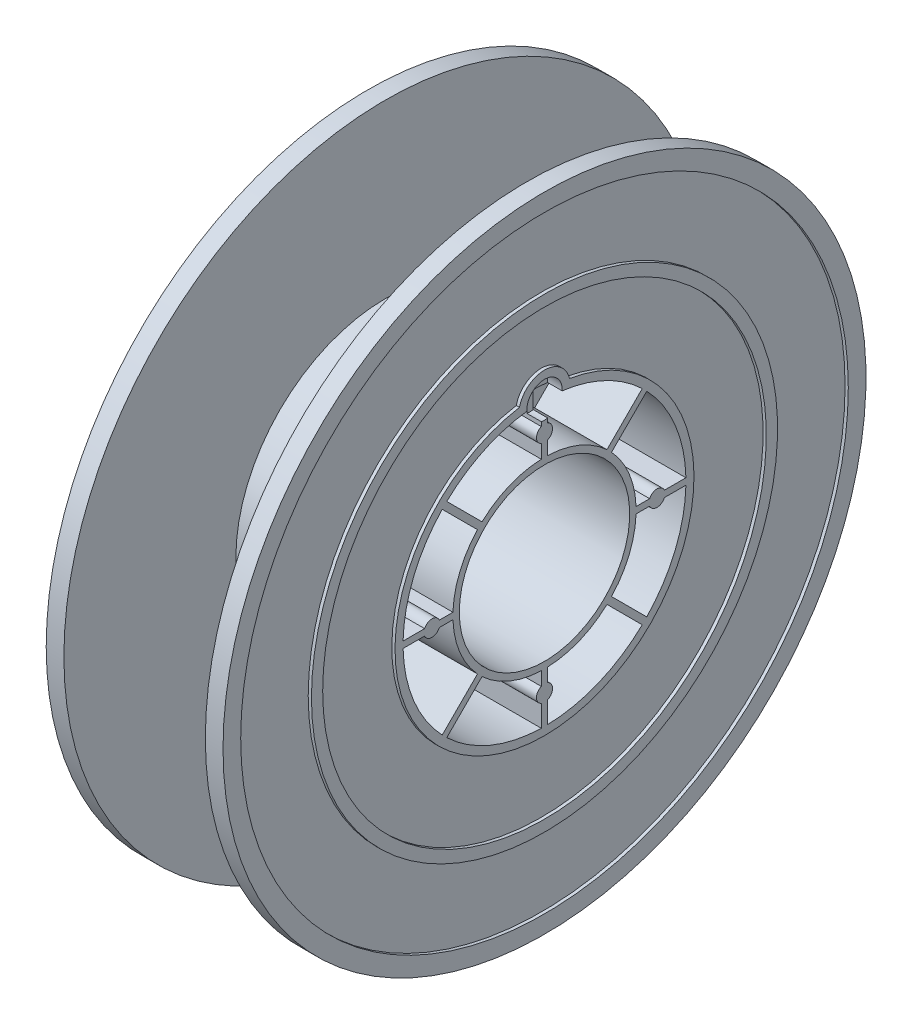
SolidWorks part; units mm, degrees
ref_plane "Front" through (0, 0, 0) normal (0, 0, 1) x (1, 0, 0)
ref_plane "Top" through (0, 0, 0) normal (0, 1, 0) x (1, 0, 0)
ref_plane "Right" through (0, 0, 0) normal (1, 0, 0) x (0, 0, -1)
sketch "Sketch1" plane through (0, 0, 0) normal (0, 0, 1) x (1, 0, 0)
  line L0 (0, 46.5) -> (0, 0) construction
  line L1 (0, 0) -> (80.9814, 0) construction
  line L2 (-27.5, 26.5) -> (27.5, 26.5)
  line L3 (27.5, 26.5) -> (27.5, 28.5)
  line L4 (27.5, 28.5) -> (-27.5, 28.5)
  line L5 (-22, 100) -> (-22, 46.5)
  line L6 (-27.5, 44) -> (27.5, 44)
  line L7 (27.5, 44) -> (27.5, 46.5)
  line L8 (27.5, 46.5) -> (26.5, 46.5)
  line L9 (26.5, 46.5) -> (26.5, 69)
  line L10 (26.5, 69) -> (27.5, 69)
  line L11 (27.5, 69) -> (27.5, 72.5)
  line L12 (27.5, 72.5) -> (26.5, 72.5)
  line L13 (26.5, 72.5) -> (26.5, 94.5)
  line L14 (27.5, 100) -> (27.5, 94.5)
  line L15 (27.5, 100) -> (22, 100)
  line L16 (22, 100) -> (22, 46.5)
  line L17 (22, 46.5) -> (-22, 46.5)
  line L18 (27.5, 94.5) -> (26.5, 94.5)
  line L19 (-27.5, 100) -> (-22, 100)
  line L20 (-27.5, 100) -> (-27.5, 94.5)
  line L21 (-27.5, 94.5) -> (-26.5, 94.5)
  line L22 (-26.5, 72.5) -> (-26.5, 94.5)
  line L23 (-27.5, 72.5) -> (-26.5, 72.5)
  line L24 (-27.5, 69) -> (-27.5, 72.5)
  line L25 (-26.5, 69) -> (-27.5, 69)
  line L26 (-26.5, 46.5) -> (-26.5, 69)
  line L27 (-27.5, 46.5) -> (-26.5, 46.5)
  line L28 (-27.5, 44) -> (-27.5, 46.5)
  line L29 (-27.5, 26.5) -> (-27.5, 28.5)
  dimension "D1" = 53
  dimension "D2" = 55
  dimension "D3" = 1
  dimension "D4" = 88
  dimension "D5" = 2.5
  dimension "D6" = 200
  dimension "D7" = 145
  dimension "D8" = 3.5
  dimension "D9" = 5.5
  dimension "D10" = 44
  dimension "D11" = 2
revolve "Revolve1" add sketch "Sketch1" angle 360 about L1
sketch "Sketch2" plane through (0, 0, 0) normal (1, 0, 0) x (0, 0, -1)
  circle A0 centre (0, 0) radius 46.5 construction
  circle A1 centre (0, 0) radius 46.5
  circle A2 centre (0, 0) radius 26.5 construction
  circle A3 centre (0, 0) radius 26.5
extrude "Boss-Extrude1" add sketch "Sketch2" along normal blind 2 from offset 3
sketch "Sketch3" plane through (-27.5, 0, 0) normal (-1, 0, 0) x (0, 0, 1)
  line L0 (0, 26.5) -> (0, 44)
  line L1 (0, -26.5) -> (0, -44)
  line L2 (26.5, 0) -> (44, 0)
  line L3 (-26.5, 0) -> (-44, 0)
  line L4 (-18.7383, 18.7383) -> (-31.1127, 31.1127)
  line L5 (18.7383, -18.7383) -> (31.1127, -31.1127)
  line L6 (18.7383, 18.7383) -> (31.1127, 31.1127)
  line L7 (-18.7383, -18.7383) -> (-31.1127, -31.1127)
  circle A0 centre (0, 0) radius 26.5 construction
  circle A1 centre (0, 0) radius 26.5 construction
  circle A2 centre (0, 0) radius 44 construction
  circle A3 centre (0, 0) radius 44 construction
  dimension "D1" = 45
extrude "Extrude-Thin1" add sketch "Sketch3" against normal up to surface (55 mm away) thin up to face at (27.5, 0, 46.5) thin type mid plane wall 2
sketch "Sketch4" plane through (27.5, 0, 0) normal (1, 0, 0) x (0, 0, -1)
  circle A0 centre (0, 0) radius 35 construction
  circle A1 centre (0, 35) radius 2.5
  circle A2 centre (35, 0) radius 2.5
  circle A3 centre (0, -35) radius 2.5
  circle A4 centre (-35, 0) radius 2.5
  dimension "D1" = 70
  dimension "D2" = 5
extrude "Boss-Extrude2" add sketch "Sketch4" against normal up to surface (22.5 mm away) up to face at (5, 32.3866, 13.415)
sketch "Sketch5" plane through (27.5, 0, 0) normal (1, 0, 0) x (0, 0, -1)
  arc A0 (7.9669, 43.2727) -> (-7.9669, 43.2727) centre (0, 44) ccw
  arc A1 (30.3976, 31.8118) -> (1, 43.9886) centre (0, 0) ccw construction
  arc A2 (30.3976, 31.8118) -> (1, 43.9886) centre (0, 0) ccw construction
  arc A3 (7.9669, 43.2727) -> (-7.9669, 43.2727) centre (0, 0) ccw
  arc A4 (-1, 43.9886) -> (-30.3976, 31.8118) centre (0, 0) ccw construction
  dimension "D1" = 16
extrude "Boss-Extrude3" add sketch "Sketch5" against normal blind 2
sketch "Sketch6" plane through (27.5, 0, 0) normal (1, 0, 0) x (0, 0, -1)
  circle A0 centre (0, 44) radius 5.5
  dimension "D1" = 11
extrude "Cut-Extrude1" cut sketch "Sketch6" against normal blind 4.5 contours A0
mirror "Mirror1" about plane through (0, 0, 0) normal (1, 0, 0) of "Cut-Extrude1", "Boss-Extrude3"
